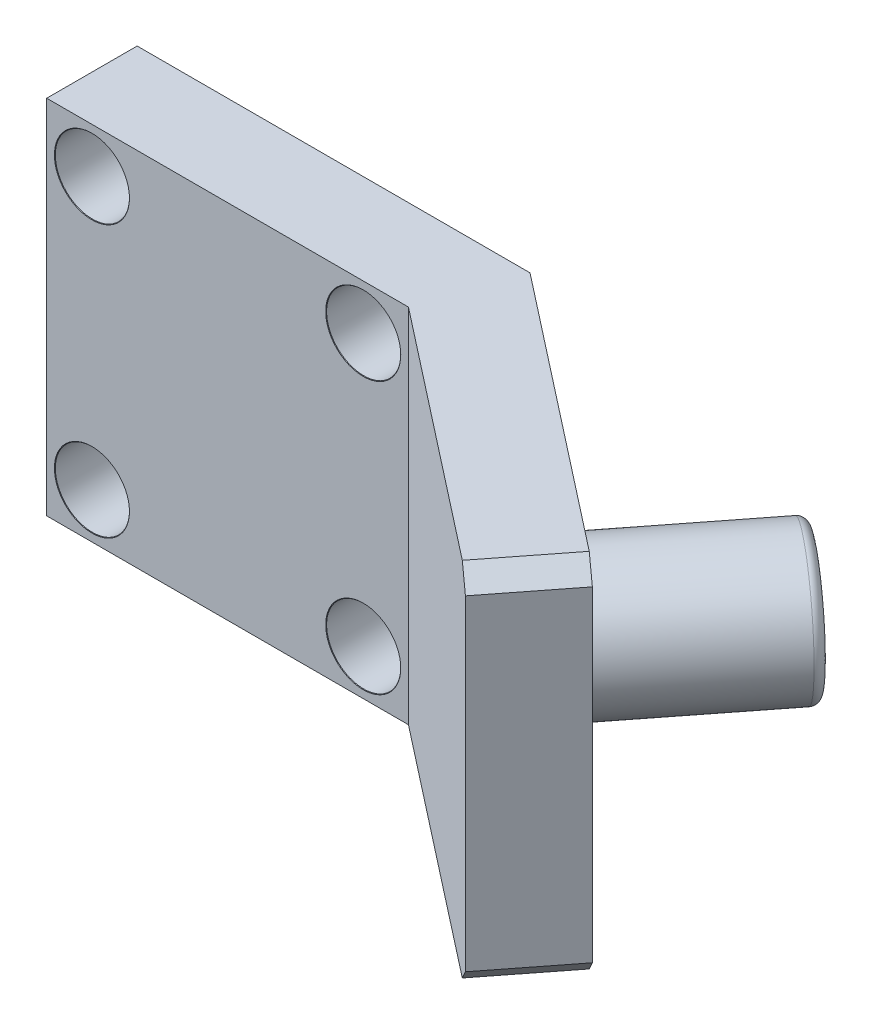
SolidWorks part; units mm, degrees
ref_plane "前视基准面" through (0, 0, 0) normal (0, 0, 1) x (1, 0, 0)
ref_plane "上视基准面" through (0, 0, 0) normal (0, 1, 0) x (1, 0, 0)
ref_plane "右视基准面" through (0, 0, 0) normal (1, 0, 0) x (0, 0, -1)
other "Configuration Table"
sketch "草图1" plane through (0, 0, 0) normal (0, 1, 0) x (1, 0, 0)
  line L0 (0, 0) -> (-21.7216, 0)
  line L1 (0, 0) -> (15.7602, -12.3132)
  line L2 (-21.7216, 0) -> (-21.7216, -5)
  line L3 (-21.7216, -5) -> (-1.7216, -5)
  line L4 (-1.7216, -5) -> (12.6819, -16.2533)
  line L5 (15.7602, -12.3132) -> (12.6819, -16.2533)
  dimension "D1" = 142
  dimension "D2" = 20
  dimension "D3" = 5
  dimension "D4" = 5
  dimension "D5" = 20
extrude "凸台-拉伸1" add sketch "草图1" along normal mid plane 20
sketch "草图2" plane through (0, 0, 5) normal (0, 0, 1) x (1, 0, 0)
  line L0 (-21.7216, 0) -> (-1.7216, 0) construction
  line L1 (-21.7216, 10) -> (-21.7216, -10) construction
  line L2 (-1.7216, 10) -> (-1.7216, -10) construction
  line L4 (-19.2216, -7.5) -> (-4.2216, -7.5) construction
  line L5 (-19.2216, -7.5) -> (-19.2216, 7.5) construction
  line L6 (-19.2216, 7.5) -> (-4.2216, 7.5) construction
  line L7 (-4.2216, -7.5) -> (-4.2216, 7.5) construction
  line L8 (-19.2216, -7.5) -> (-4.2216, 7.5) construction
  line L9 (-19.2216, 7.5) -> (-4.2216, -7.5) construction
  point P6 (-11.7216, 0)
  dimension "D1" = 15
  dimension "D2" = 15
hole_wizard "Ø4.1 (4.1) 直径孔1" positions "3D草图1" profile "草图3" hole size "Ø4.1" standard "GB" end condition through all
sketch3d "3D草图1"
  point P0 (-19.2216, 7.5, 5)
  point P3 (-4.2216, 7.5, 5)
  point P6 (-4.2216, -7.5, 5)
  point P9 (-19.2216, -7.5, 5)
sketch "草图3" plane through (-19.2216, 7.5, 5) normal (1, 0, 0) x (0, -1, 0)
  line L0 (0, 0) -> (0, 5)
  line L1 (0, 5) -> (2.05, 5)
  line L2 (2.05, 5) -> (2.05, 0.025)
  line L3 (2.05, 0.025) -> (2.075, 0)
  line L5 (2.075, 0) -> (0, 0)
  line L6 (-2.05, 0.025) -> (-2.075, 0) construction
  line L11 (0, -6.35) -> (0, 107.95) construction
  dimension "通孔孔直径" = 4.1
  dimension "通孔孔深度" = 5
  dimension "近端锥形沉头孔直径" = 4.15
  dimension "近端锥形沉头孔角度" = 90
sketch "草图4" plane through (0, 0, 0) normal (0.6157, 0, -0.788) x (-0.788, 0, -0.6157)
  line L0 (-20, 0) -> (0, 0) construction
  line L1 (-20, 10) -> (-20, -10) construction
  circle A0 centre (-10, 0) radius 3.75
  dimension "D1" = 7.5
extrude "凸台-拉伸2" add sketch "草图4" along normal blind 10
fillet "圆角1" radius 0.5 1 edges at (11.0817, 0, -4.0322)
chamfer "倒角1" distance 1 angle 45 2 edges at (14.2211, -10, 14.2833) (14.2211, 10, 14.2833)
